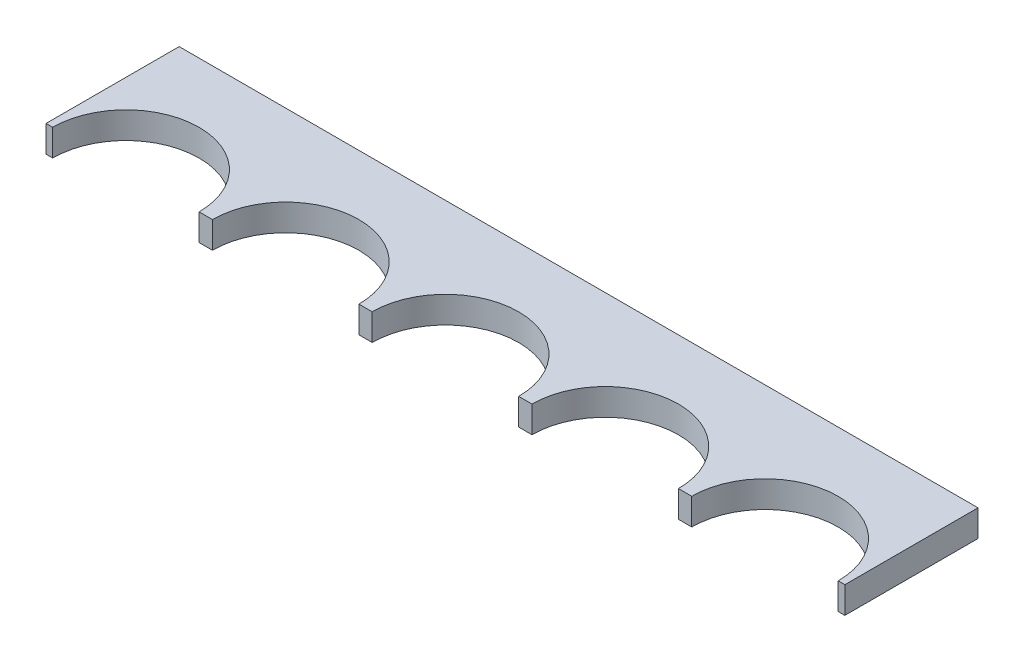
SolidWorks part; units mm, degrees
ref_plane "Plan de face" through (0, 0, 0) normal (0, 0, 1) x (1, 0, 0)
ref_plane "Plan de dessus" through (0, 0, 0) normal (0, 1, 0) x (1, 0, 0)
ref_plane "Plan de droite" through (0, 0, 0) normal (1, 0, 0) x (0, 0, -1)
sketch "Esquisse1" plane through (0, 0, 0) normal (0, 1, 0) x (1, 0, 0)
  line L1 (150, -25) -> (-150, -25)
  line L2 (150, -25) -> (150, 25)
  line L3 (150, 25) -> (-150, 25)
  line L4 (-150, -25) -> (-150, 25)
  line L5 (150, -25) -> (-150, 25) construction
  line L6 (150, 25) -> (-150, -25) construction
  line L7 (-150, -25) -> (150, -25) construction
  circle A0 centre (-120, -25) radius 27.5
  circle A1 centre (-60, -25) radius 27.5
  circle A2 centre (0, -25) radius 27.5
  circle A3 centre (60, -25) radius 27.5
  circle A4 centre (120, -25) radius 27.5
  point P0 (0, 0)
  dimension "D4" = 55
  dimension "D1" = 300
  dimension "D2" = 50
  dimension "D3" = 5
  dimension "D5" = 30
  dimension "D6" = 30
extrude "Boss.-Extru.1" add sketch "Esquisse1" along normal blind 10 contours A4 L1 L2 L3 L4 A0 A1 A2 A3
